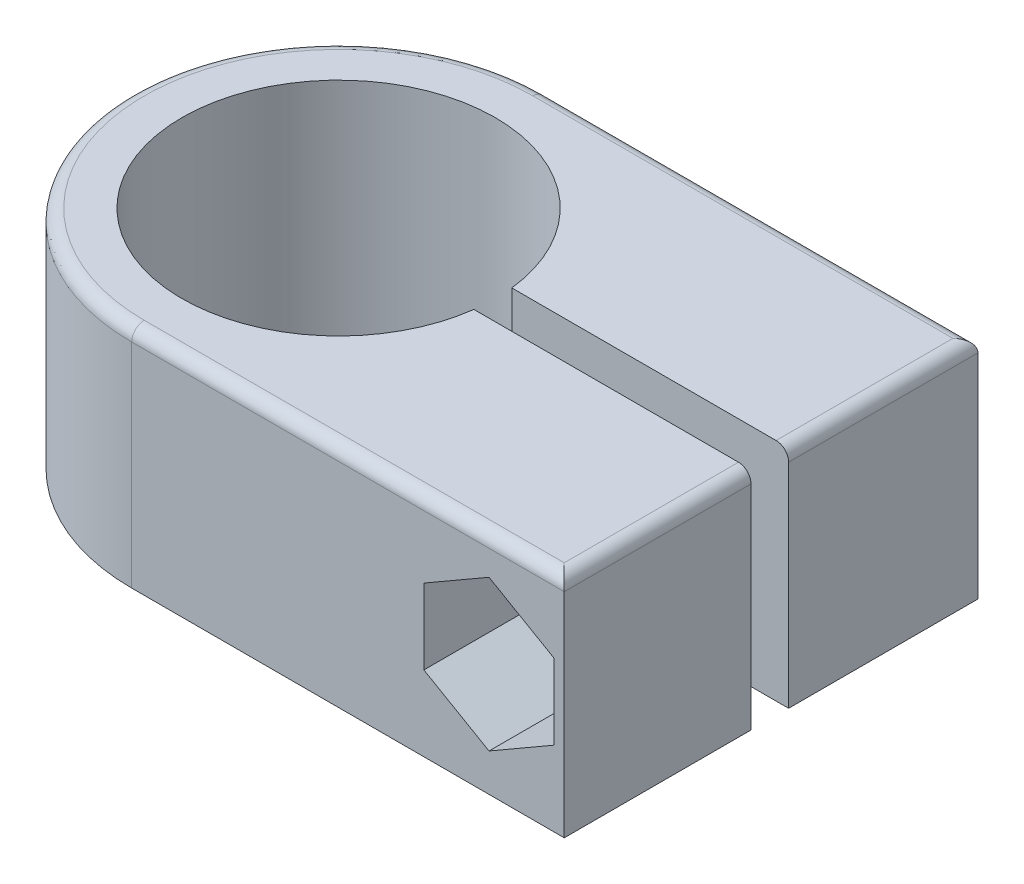
SolidWorks part; units mm, degrees
material "Silicon Rubber"
ref_plane "Front Plane" through (0, 0, 0) normal (0, 0, 1) x (1, 0, 0)
ref_plane "Top Plane" through (0, 0, 0) normal (0, 1, 0) x (1, 0, 0)
ref_plane "Right Plane" through (0, 0, 0) normal (1, 0, 0) x (0, 0, -1)
sketch "Sketch1" plane through (0, 0, 0) normal (0, 1, 0) x (1, 0, 0)
  line L1 (0, -16.5) -> (34.5, -16.5)
  line L2 (0, 16.5) -> (34.5, 16.5)
  line L3 (34.5, -16.5) -> (34.5, -1.6055)
  line L4 (34.5, 1.3945) -> (34.5, 16.5)
  line L5 (12.3965, -1.6055) -> (34.5, -1.6055)
  line L7 (12.422, 1.3945) -> (34.5, 1.3945)
  line L9 (12.4596, -1.0038) -> (34.5, 0.9292) construction
  line L10 (12.4749, 0.7914) -> (34.5, -1.1402) construction
  arc A0 (12.422, 1.3945) -> (12.3965, -1.6055) centre (0, 0) ccw
  arc A1 (0, 16.5) -> (0, -16.5) centre (0, 0) ccw
  circle A2 centre (0, 0) radius 16.5 construction
  circle A3 centre (0, 0) radius 12.5 construction
  point P4 (22.702, -0.1055)
  dimension "D1" = 25
  dimension "D3" = 34.5
  dimension "D2" = 4
extrude "Boss-Extrude1" add sketch "Sketch1" along normal blind 18
fillet "Fillet1" radius 1 5 edges at (17.25, 18, -16.5) (-16.5, 18, 0) (17.25, 18, 16.5) (34.5, 18, 9.0528) (34.5, 18, -8.9472)
sketch "Sketch2" plane through (0, 0, 16.5) normal (0, 0, 1) x (1, 0, 0)
  line L0 (0, 0) -> (34.5, 0) construction
  line L1 (28.5, 15) -> (23.3038, 12)
  line L2 (23.3038, 12) -> (23.3038, 6)
  line L3 (23.3038, 6) -> (28.5, 3)
  line L4 (28.5, 3) -> (33.6962, 6)
  line L5 (33.6962, 6) -> (33.6962, 12)
  line L6 (33.6962, 12) -> (28.5, 15)
  line L7 (34.5, 17) -> (34.5, 0) construction
  circle A0 centre (28.5, 9) radius 6 construction
  dimension "D1" = 9
  dimension "D2" = 6
extrude "Cut-Extrude1" cut sketch "Sketch2" against normal blind 10 and the other way through all
mirror "Mirror1" about plane through (0, 0, 0) normal (0, 0, 1) of "Cut-Extrude1"
